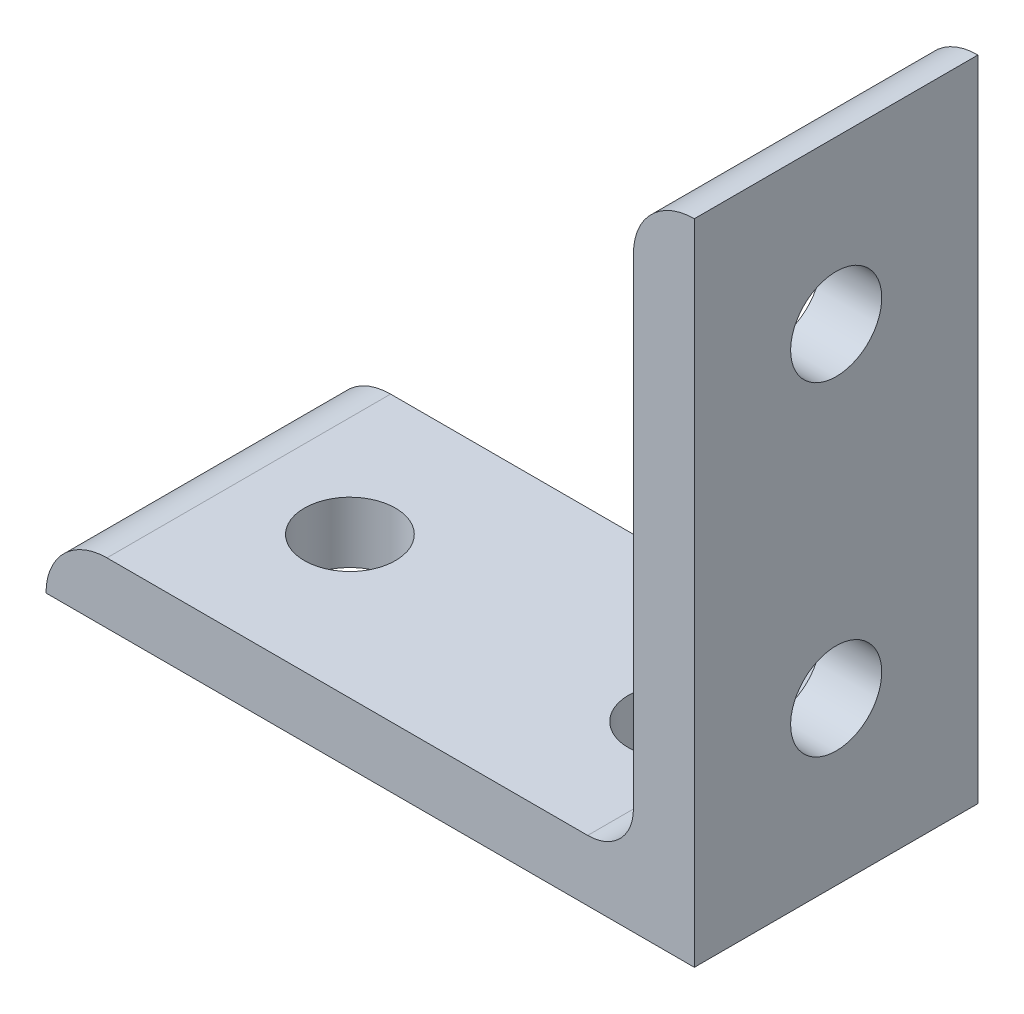
SolidWorks part; units mm, degrees
ref_plane "Front Plane" through (0, 0, 0) normal (0, 0, 1) x (1, 0, 0)
ref_plane "Top Plane" through (0, 0, 0) normal (0, 1, 0) x (1, 0, 0)
ref_plane "Right Plane" through (0, 0, 0) normal (1, 0, 0) x (0, 0, -1)
sketch "Sketch1" plane through (0, 0, 0) normal (0, 0, 1) x (1, 0, 0)
  line L0 (0, 0) -> (0, 50.8)
  line L1 (0, 0) -> (-50.8, 0)
  line L2 (-46.0248, 4.7752) -> (-8.3566, 4.7752)
  line L3 (-4.7752, 8.3566) -> (-4.7752, 46.0248)
  arc A0 (-50.8, 0) -> (-46.0248, 4.7752) centre (-46.0248, 0) cw
  arc A1 (-4.7752, 46.0248) -> (0, 50.8) centre (0, 46.0248) cw
  arc A2 (-8.3566, 4.7752) -> (-4.7752, 8.3566) centre (-8.3566, 8.3566) ccw
  point P11 (-27.1907, 4.7752)
  point P12 (-4.7752, 27.1907)
  dimension "D1" = 4.7752
  dimension "D3" = 3.5814
  dimension "D" = 4.7752
  dimension "D2" = 4.7752
  dimension "B" = 50.8
  dimension "C" = 50.8
extrude "Extrude1" add sketch "Sketch1" against normal mid plane 22.225
sketch "Sketch2" [suppressed] plane through (0, 6.35, 0) normal (0, 1, 0) x (1, 0, 0)
  circle A0 centre (-20.8407, 0) radius 4.1656
  dimension "hole" = 7.1374
extrude "Cut-Extrude1" [suppressed] cut sketch "Sketch2" against normal through all
sketch "Sketch3" [suppressed] plane through (-6.35, 0, 0) normal (-1, 0, 0) x (0, 0, 1)
  circle A0 centre (0, 20.8407) radius 4.1656
  dimension "D1" = 7.1374
extrude "Cut-Extrude2" [suppressed] cut sketch "Sketch3" against normal through all
sketch "Sketch4" plane through (0, 4.7752, 0) normal (0, 1, 0) x (1, 0, 0)
  line L0 (-50.8, 0) -> (-25.4, 0) construction
  line L1 (-25.4, 0) -> (0, 0) construction
  line L2 (-50.8, 11.1125) -> (-50.8, -11.1125) construction
  line L3 (0, 11.1125) -> (0, -11.1125) construction
  circle A0 centre (-12.7, 0) radius 3.5687
  circle A1 centre (-38.1, 0) radius 3.5687
  dimension "D1" = 7.1374
  dimension "D3" = 25.4
extrude "Cut-Extrude3" cut sketch "Sketch4" against normal through all
sketch "Sketch5" plane through (-4.7752, 0, 0) normal (-1, 0, 0) x (0, 0, 1)
  line L0 (0, 0) -> (0, 25.4) construction
  line L1 (0, 25.4) -> (0, 50.8) construction
  line L2 (-11.1125, 50.8) -> (11.1125, 50.8) construction
  line L3 (-11.1125, 0) -> (11.1125, 0) construction
  circle A0 centre (0, 38.1) radius 3.5687
  circle A1 centre (0, 12.7) radius 3.5687
  dimension "D1" = 7.1374
  dimension "D3" = 25.4
extrude "Cut-Extrude4" cut sketch "Sketch5" against normal through all
sketch "Sketch6" [suppressed] plane through (0, 6.35, 0) normal (0, 1, 0) x (1, 0, 0)
  line L0 (-20.8407, 23.2156) -> (-20.8407, 35.687) construction
  line L1 (-9.9314, 35.687) -> (-31.75, 35.687) construction
  line L2 (-20.8407, -23.2156) -> (-20.8407, -35.687) construction
  line L3 (-9.9314, -35.687) -> (-31.75, -35.687) construction
  circle A0 centre (-20.8407, 19.05) radius 4.1656
  circle A1 centre (-20.8407, -19.05) radius 4.1656
  dimension "D1" = 7.1374
  dimension "distance" = 25.4
extrude "Cut-Extrude5" [suppressed] cut sketch "Sketch6" against normal through all
sketch "Sketch7" [suppressed] plane through (-6.35, 0, 0) normal (-1, 0, 0) x (0, 0, 1)
  line L0 (23.2156, 20.8407) -> (35.687, 20.8407) construction
  line L1 (35.687, 31.75) -> (35.687, 9.9314) construction
  line L2 (-23.2156, 20.8407) -> (-35.687, 20.8407) construction
  line L3 (-35.687, 31.75) -> (-35.687, 9.9314) construction
  circle A0 centre (-19.05, 20.8407) radius 4.1656
  circle A1 centre (19.05, 20.8407) radius 4.1656
  dimension "D2" = 7.1374
  dimension "D1" = 25.4
extrude "Cut-Extrude6" [suppressed] cut sketch "Sketch7" against normal through all
sketch "Sketch8" [suppressed] plane through (0, 4.7752, 0) normal (0, 1, 0) x (1, 0, 0)
  line L0 (-46.0248, 0) -> (-27.1907, 0) construction
  line L1 (-27.1907, 0) -> (-8.3566, 0) construction
  line L2 (-17.7737, 0) -> (-17.7737, -12.7) construction
  line L3 (-36.6078, 0) -> (-36.6078, -12.7) construction
  circle A0 centre (-36.6078, -12.7) radius 3.5687
  circle A1 centre (-17.7737, -12.7) radius 3.5687
  circle A2 centre (-17.7737, 12.7) radius 3.5687
  circle A3 centre (-36.6078, 12.7) radius 3.5687
  dimension "D1" = 7.1374
  dimension "distance" = 42.6089
extrude "Cut-Extrude7" [suppressed] cut sketch "Sketch8" against normal through all
sketch "Sketch9" [suppressed] plane through (-4.7752, 0, 0) normal (-1, 0, 0) x (0, 0, 1)
  line L0 (0, 8.3566) -> (0, 27.1907) construction
  line L1 (0, 27.1907) -> (0, 46.0248) construction
  line L2 (0, 36.6078) -> (12.7, 36.6078) construction
  line L3 (0, 17.7737) -> (12.7, 17.7737) construction
  circle A0 centre (12.7, 17.7737) radius 3.5687
  circle A1 centre (12.7, 36.6078) radius 3.5687
  circle A2 centre (-12.7, 17.7737) radius 3.5687
  circle A3 centre (-12.7, 36.6078) radius 3.5687
  dimension "D1" = 7.1374
  dimension "D2" = 42.6089
extrude "Cut-Extrude8" [suppressed] cut sketch "Sketch9" against normal through all
equation "\"D2@Sketch1\" = \"D@Sketch1\""
equation "\"D3@Sketch1\" = \"D1@Sketch1\"*.750"
equation "\"D1@Sketch3\" = \"hole@Sketch2\""
equation "\"D1@Sketch4\" = \"hole@Sketch2\""
equation "\"D1@Sketch5\" = \"hole@Sketch2\""
equation "\"D1@Sketch6\" = \"hole@Sketch2\""
equation "\"D2@Sketch7\" = \"hole@Sketch2\""
equation "\"D1@Sketch7\" = \"distance@Sketch6\""
equation "\"D1@Sketch8\" = \"hole@Sketch2\""
equation "\"D1@Sketch9\" = \"hole@Sketch2\""
equation "\"D2@Sketch9\" = \"distance@Sketch8\""
